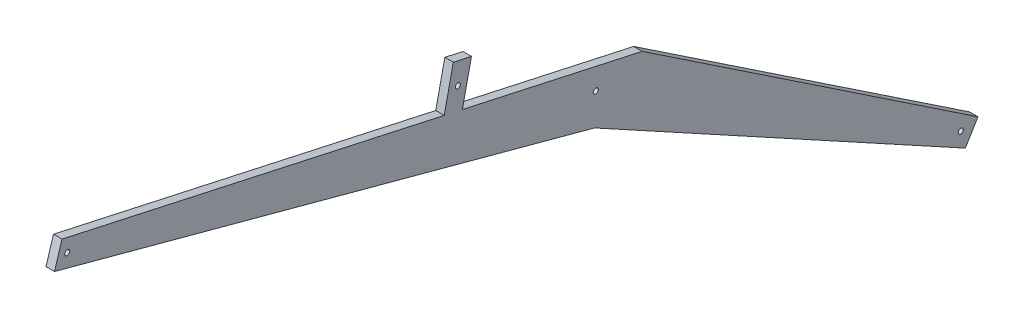
SolidWorks part; units mm, degrees
ref_plane "前视基准面" through (0, 0, 0) normal (0, 0, 1) x (1, 0, 0)
ref_plane "上视基准面" through (0, 0, 0) normal (0, 1, 0) x (1, 0, 0)
ref_plane "右视基准面" through (0, 0, 0) normal (1, 0, 0) x (0, 0, -1)
other "Configuration Table"
sketch "草图1" plane through (0, 0, 0) normal (1, 0, 0) x (0, 0, -1)
  line L0 (-125.6653, 32.6339) -> (10.9154, 2.6256)
  line L1 (10.9154, 2.6256) -> (89.9829, -50.249)
  line L2 (89.9829, -50.249) -> (87.0073, -55.1568)
  line L3 (87.0073, -55.1568) -> (-0.2862, -7.394)
  line L4 (-0.2862, -7.394) -> (-127.4273, 26.8985)
  line L5 (-127.4273, 26.8985) -> (-125.6653, 32.6339)
  line L7 (0, 0) -> (-126.5463, 29.7662)
  line L8 (88.4951, -52.7029) -> (85.9298, -51.1476)
  circle A0 centre (0, 0) radius 0.6
  circle A1 centre (85.9298, -51.1476) radius 0.6
  circle A2 centre (-124.4283, 29.268) radius 0.6
  dimension "D1" = 1.2
  dimension "D5" = 1.2
  dimension "D10" = 1.2
  dimension "D2" = 100
  dimension "D3" = 3
  dimension "D4" = 3
  dimension "D6" = 3
  dimension "D9" = 130
  dimension "D11" = 6
extrude "凸台-拉伸1" add sketch "草图1" along normal blind 2
sketch "草图2" plane through (0, 4.7925, -1.053) normal (0, 0.9767, -0.2146) x (1, 0, 0)
  line L0 (2, -129.7408) -> (2, 10.0977) construction
  line L1 (0, -33.2351) -> (2, -33.2351)
  line L2 (0, -33.2351) -> (0, -37.6068)
  line L3 (0, -37.6068) -> (2, -37.6068)
  line L4 (2, -33.2351) -> (2, -37.6068)
extrude "凸台-拉伸2" add sketch "草图2" along normal blind 10 contours L3 L4 L1 L2
sketch "草图3" plane through (2, 0, 0) normal (1, 0, 0) x (0, 0, -1)
  line L0 (-32.4698, 17.2771) -> (-31.3969, 22.1606)
  line L1 (-29.262, 21.6916) -> (-33.5318, 22.6297) construction
  line L2 (-125.6653, 32.6339) -> (-35.6777, 12.8627) construction
  circle A0 centre (-32.4698, 17.2771) radius 0.6
  dimension "D1" = 1.2
  dimension "D2" = 5
extrude "切除-拉伸1" cut sketch "草图3" against normal through all contours A0
